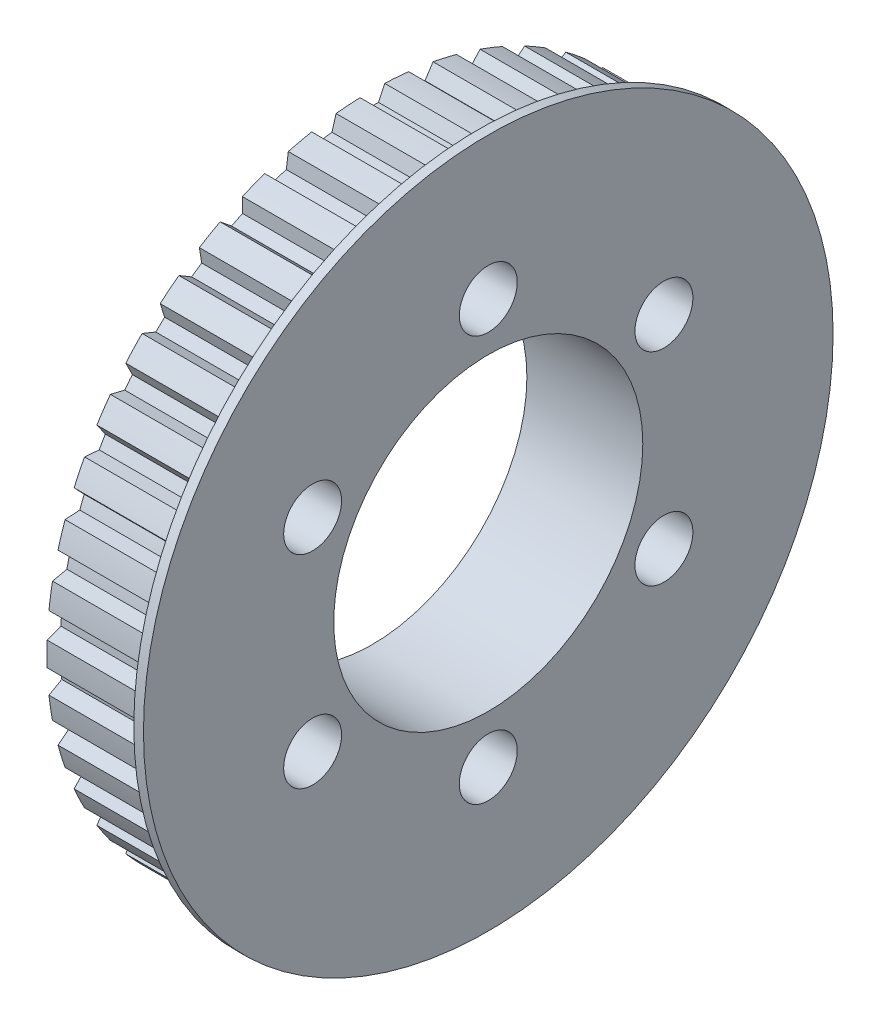
SolidWorks part; units mm, degrees
ref_plane "Front Plane" through (0, 0, 0) normal (0, 0, 1) x (1, 0, 0)
ref_plane "Top Plane" through (0, 0, 0) normal (0, 1, 0) x (1, 0, 0)
ref_plane "Right Plane" through (0, 0, 0) normal (1, 0, 0) x (0, 0, -1)
sketch "Sketch1" plane through (0, 0, 0) normal (1, 0, 0) x (0, 0, -1)
  line L0 (0, 33.705) -> (0, 0) construction
  circle A0 centre (0, 0) radius 33.705
  circle A1 centre (0, 0) radius 16
  point P19 (0, 0)
  dimension "D1" = 67.41
  dimension "D2" = 32
extrude "Boss-Extrude1" add sketch "Sketch1" along normal blind 11
sketch "Sketch2" plane through (0, 0, 0) normal (-1, 0, 0) x (0, 0, 1)
  line L0 (0, 0) -> (0, 33.705) construction
  line L1 (1.2794, 33.6807) -> (0.635, 32.2988)
  line L2 (-1.2794, 33.6807) -> (-0.635, 32.2988)
  line L3 (6.2849, 33.1138) -> (5.4417, 31.8434)
  line L4 (3.7548, 33.4952) -> (4.186, 32.0326)
  line L5 (11.1501, 31.8073) -> (10.127, 30.6767)
  line L6 (8.705, 32.5615) -> (8.9135, 31.051)
  line L7 (15.7662, 29.7902) -> (14.586, 28.8247)
  line L8 (13.4608, 30.9004) -> (13.4418, 29.3757)
  line L9 (20.0301, 27.1076) -> (18.7192, 26.3288)
  line L10 (17.916, 28.549) -> (17.6699, 27.0442)
  line L11 (23.8465, 23.8195) -> (22.4342, 23.2448)
  line L12 (21.9709, 25.5599) -> (21.5033, 24.1085)
  line L13 (27.1303, 19.9993) -> (25.6481, 19.6415)
  line L14 (25.535, 21.9998) -> (24.8563, 20.6344)
  line L15 (29.808, 15.7324) -> (28.289, 15.5995)
  line L16 (28.5287, 17.9483) -> (27.6541, 16.6993)
  line L17 (31.8199, 11.114) -> (30.298, 11.209)
  line L18 (30.8851, 13.4959) -> (29.8341, 12.3911)
  line L19 (33.121, 6.2474) -> (31.6303, 6.5681)
  line L20 (32.5516, 8.742) -> (31.3477, 7.8062)
  line L21 (33.6821, 1.2412) -> (32.2559, 1.7805)
  line L22 (33.4909, 3.7928) -> (32.161, 3.0469)
  line L23 (33.4909, -3.7928) -> (32.161, -3.0469)
  line L24 (33.6821, -1.2412) -> (32.2559, -1.7805)
  line L25 (32.5516, -8.742) -> (31.3477, -7.8062)
  line L26 (33.121, -6.2474) -> (31.6303, -6.5681)
  line L27 (30.8851, -13.4959) -> (29.8341, -12.3911)
  line L28 (31.8199, -11.114) -> (30.298, -11.209)
  line L29 (28.5287, -17.9483) -> (27.6541, -16.6993)
  line L30 (29.808, -15.7324) -> (28.289, -15.5995)
  line L31 (25.535, -21.9998) -> (24.8563, -20.6344)
  line L32 (27.1303, -19.9993) -> (25.6481, -19.6415)
  line L33 (21.9709, -25.5599) -> (21.5033, -24.1085)
  line L34 (23.8465, -23.8195) -> (22.4342, -23.2448)
  line L35 (17.916, -28.549) -> (17.6699, -27.0442)
  line L36 (20.0301, -27.1076) -> (18.7192, -26.3288)
  line L37 (13.4608, -30.9004) -> (13.4418, -29.3757)
  line L38 (15.7662, -29.7902) -> (14.586, -28.8247)
  line L39 (8.705, -32.5615) -> (8.9135, -31.051)
  line L40 (11.1501, -31.8073) -> (10.127, -30.6767)
  line L41 (3.7548, -33.4952) -> (4.186, -32.0326)
  line L42 (6.2849, -33.1138) -> (5.4417, -31.8434)
  line L43 (-1.2794, -33.6807) -> (-0.635, -32.2988)
  line L44 (1.2794, -33.6807) -> (0.635, -32.2988)
  line L45 (-6.2849, -33.1138) -> (-5.4417, -31.8434)
  line L46 (-3.7548, -33.4952) -> (-4.186, -32.0326)
  line L47 (-11.1501, -31.8073) -> (-10.127, -30.6767)
  line L48 (-8.705, -32.5615) -> (-8.9135, -31.051)
  line L49 (-15.7662, -29.7902) -> (-14.586, -28.8247)
  line L50 (-13.4608, -30.9004) -> (-13.4418, -29.3757)
  line L51 (-20.0301, -27.1076) -> (-18.7192, -26.3288)
  line L52 (-17.916, -28.549) -> (-17.6699, -27.0442)
  line L53 (-23.8465, -23.8195) -> (-22.4342, -23.2448)
  line L54 (-21.9709, -25.5599) -> (-21.5033, -24.1085)
  line L55 (-27.1303, -19.9993) -> (-25.6481, -19.6415)
  line L56 (-25.535, -21.9998) -> (-24.8563, -20.6344)
  line L57 (-29.808, -15.7324) -> (-28.289, -15.5995)
  line L58 (-28.5287, -17.9483) -> (-27.6541, -16.6993)
  line L59 (-31.8199, -11.114) -> (-30.298, -11.209)
  line L60 (-30.8851, -13.4959) -> (-29.8341, -12.3911)
  line L61 (-33.121, -6.2474) -> (-31.6303, -6.5681)
  line L62 (-32.5516, -8.742) -> (-31.3477, -7.8062)
  line L63 (-33.6821, -1.2412) -> (-32.2559, -1.7805)
  line L64 (-33.4909, -3.7928) -> (-32.161, -3.0469)
  line L65 (-33.4909, 3.7928) -> (-32.161, 3.0469)
  line L66 (-33.6821, 1.2412) -> (-32.2559, 1.7805)
  line L67 (-32.5516, 8.742) -> (-31.3477, 7.8062)
  line L68 (-33.121, 6.2474) -> (-31.6303, 6.5681)
  line L69 (-30.8851, 13.4959) -> (-29.8341, 12.3911)
  line L70 (-31.8199, 11.114) -> (-30.298, 11.209)
  line L71 (-28.5287, 17.9483) -> (-27.6541, 16.6993)
  line L72 (-29.808, 15.7324) -> (-28.289, 15.5995)
  line L73 (-25.535, 21.9998) -> (-24.8563, 20.6344)
  line L74 (-27.1303, 19.9993) -> (-25.6481, 19.6415)
  line L75 (-21.9709, 25.5599) -> (-21.5033, 24.1085)
  line L76 (-23.8465, 23.8195) -> (-22.4342, 23.2448)
  line L77 (-17.916, 28.549) -> (-17.6699, 27.0442)
  line L78 (-20.0301, 27.1076) -> (-18.7192, 26.3288)
  line L79 (-13.4608, 30.9004) -> (-13.4418, 29.3757)
  line L80 (-15.7662, 29.7902) -> (-14.586, 28.8247)
  line L81 (-8.705, 32.5615) -> (-8.9135, 31.051)
  line L82 (-11.1501, 31.8073) -> (-10.127, 30.6767)
  line L83 (-3.7548, 33.4952) -> (-4.186, 32.0326)
  line L84 (-6.2849, 33.1138) -> (-5.4417, 31.8434)
  circle A0 centre (0, 0) radius 33.705 construction
  arc A1 (1.2794, 33.6807) -> (-1.2794, 33.6807) centre (0, 0) ccw
  arc A2 (0.635, 32.2988) -> (-0.635, 32.2988) centre (0, 0) ccw
  arc A3 (6.2849, 33.1138) -> (3.7548, 33.4952) centre (0, 0) ccw
  arc A4 (5.4417, 31.8434) -> (4.186, 32.0326) centre (0, 0) ccw
  arc A5 (11.1501, 31.8073) -> (8.705, 32.5615) centre (0, 0) ccw
  arc A6 (10.127, 30.6767) -> (8.9135, 31.051) centre (0, 0) ccw
  arc A7 (15.7662, 29.7902) -> (13.4608, 30.9004) centre (0, 0) ccw
  arc A8 (14.586, 28.8247) -> (13.4418, 29.3757) centre (0, 0) ccw
  arc A9 (20.0301, 27.1076) -> (17.916, 28.549) centre (0, 0) ccw
  arc A10 (18.7192, 26.3288) -> (17.6699, 27.0442) centre (0, 0) ccw
  arc A11 (23.8465, 23.8195) -> (21.9709, 25.5599) centre (0, 0) ccw
  arc A12 (22.4342, 23.2448) -> (21.5033, 24.1085) centre (0, 0) ccw
  arc A13 (27.1303, 19.9993) -> (25.535, 21.9998) centre (0, 0) ccw
  arc A14 (25.6481, 19.6415) -> (24.8563, 20.6344) centre (0, 0) ccw
  arc A15 (29.808, 15.7324) -> (28.5287, 17.9483) centre (0, 0) ccw
  arc A16 (28.289, 15.5995) -> (27.6541, 16.6993) centre (0, 0) ccw
  arc A17 (31.8199, 11.114) -> (30.8851, 13.4959) centre (0, 0) ccw
  arc A18 (30.298, 11.209) -> (29.8341, 12.3911) centre (0, 0) ccw
  arc A19 (33.121, 6.2474) -> (32.5516, 8.742) centre (0, 0) ccw
  arc A20 (31.6303, 6.5681) -> (31.3477, 7.8062) centre (0, 0) ccw
  arc A21 (33.6821, 1.2412) -> (33.4909, 3.7928) centre (0, 0) ccw
  arc A22 (32.2559, 1.7805) -> (32.161, 3.0469) centre (0, 0) ccw
  arc A23 (33.4909, -3.7928) -> (33.6821, -1.2412) centre (0, 0) ccw
  arc A24 (32.161, -3.0469) -> (32.2559, -1.7805) centre (0, 0) ccw
  arc A25 (32.5516, -8.742) -> (33.121, -6.2474) centre (0, 0) ccw
  arc A26 (31.3477, -7.8062) -> (31.6303, -6.5681) centre (0, 0) ccw
  arc A27 (30.8851, -13.4959) -> (31.8199, -11.114) centre (0, 0) ccw
  arc A28 (29.8341, -12.3911) -> (30.298, -11.209) centre (0, 0) ccw
  arc A29 (28.5287, -17.9483) -> (29.808, -15.7324) centre (0, 0) ccw
  arc A30 (27.6541, -16.6993) -> (28.289, -15.5995) centre (0, 0) ccw
  arc A31 (25.535, -21.9998) -> (27.1303, -19.9993) centre (0, 0) ccw
  arc A32 (24.8563, -20.6344) -> (25.6481, -19.6415) centre (0, 0) ccw
  arc A33 (21.9709, -25.5599) -> (23.8465, -23.8195) centre (0, 0) ccw
  arc A34 (21.5033, -24.1085) -> (22.4342, -23.2448) centre (0, 0) ccw
  arc A35 (17.916, -28.549) -> (20.0301, -27.1076) centre (0, 0) ccw
  arc A36 (17.6699, -27.0442) -> (18.7192, -26.3288) centre (0, 0) ccw
  arc A37 (13.4608, -30.9004) -> (15.7662, -29.7902) centre (0, 0) ccw
  arc A38 (13.4418, -29.3757) -> (14.586, -28.8247) centre (0, 0) ccw
  arc A39 (8.705, -32.5615) -> (11.1501, -31.8073) centre (0, 0) ccw
  arc A40 (8.9135, -31.051) -> (10.127, -30.6767) centre (0, 0) ccw
  arc A41 (3.7548, -33.4952) -> (6.2849, -33.1138) centre (0, 0) ccw
  arc A42 (4.186, -32.0326) -> (5.4417, -31.8434) centre (0, 0) ccw
  arc A43 (-1.2794, -33.6807) -> (1.2794, -33.6807) centre (0, 0) ccw
  arc A44 (-0.635, -32.2988) -> (0.635, -32.2988) centre (0, 0) ccw
  arc A45 (-6.2849, -33.1138) -> (-3.7548, -33.4952) centre (0, 0) ccw
  arc A46 (-5.4417, -31.8434) -> (-4.186, -32.0326) centre (0, 0) ccw
  arc A47 (-11.1501, -31.8073) -> (-8.705, -32.5615) centre (0, 0) ccw
  arc A48 (-10.127, -30.6767) -> (-8.9135, -31.051) centre (0, 0) ccw
  arc A49 (-15.7662, -29.7902) -> (-13.4608, -30.9004) centre (0, 0) ccw
  arc A50 (-14.586, -28.8247) -> (-13.4418, -29.3757) centre (0, 0) ccw
  arc A51 (-20.0301, -27.1076) -> (-17.916, -28.549) centre (0, 0) ccw
  arc A52 (-18.7192, -26.3288) -> (-17.6699, -27.0442) centre (0, 0) ccw
  arc A53 (-23.8465, -23.8195) -> (-21.9709, -25.5599) centre (0, 0) ccw
  arc A54 (-22.4342, -23.2448) -> (-21.5033, -24.1085) centre (0, 0) ccw
  arc A55 (-27.1303, -19.9993) -> (-25.535, -21.9998) centre (0, 0) ccw
  arc A56 (-25.6481, -19.6415) -> (-24.8563, -20.6344) centre (0, 0) ccw
  arc A57 (-29.808, -15.7324) -> (-28.5287, -17.9483) centre (0, 0) ccw
  arc A58 (-28.289, -15.5995) -> (-27.6541, -16.6993) centre (0, 0) ccw
  arc A59 (-31.8199, -11.114) -> (-30.8851, -13.4959) centre (0, 0) ccw
  arc A60 (-30.298, -11.209) -> (-29.8341, -12.3911) centre (0, 0) ccw
  arc A61 (-33.121, -6.2474) -> (-32.5516, -8.742) centre (0, 0) ccw
  arc A62 (-31.6303, -6.5681) -> (-31.3477, -7.8062) centre (0, 0) ccw
  arc A63 (-33.6821, -1.2412) -> (-33.4909, -3.7928) centre (0, 0) ccw
  arc A64 (-32.2559, -1.7805) -> (-32.161, -3.0469) centre (0, 0) ccw
  arc A65 (-33.4909, 3.7928) -> (-33.6821, 1.2412) centre (0, 0) ccw
  arc A66 (-32.161, 3.0469) -> (-32.2559, 1.7805) centre (0, 0) ccw
  arc A67 (-32.5516, 8.742) -> (-33.121, 6.2474) centre (0, 0) ccw
  arc A68 (-31.3477, 7.8062) -> (-31.6303, 6.5681) centre (0, 0) ccw
  arc A69 (-30.8851, 13.4959) -> (-31.8199, 11.114) centre (0, 0) ccw
  arc A70 (-29.8341, 12.3911) -> (-30.298, 11.209) centre (0, 0) ccw
  arc A71 (-28.5287, 17.9483) -> (-29.808, 15.7324) centre (0, 0) ccw
  arc A72 (-27.6541, 16.6993) -> (-28.289, 15.5995) centre (0, 0) ccw
  arc A73 (-25.535, 21.9998) -> (-27.1303, 19.9993) centre (0, 0) ccw
  arc A74 (-24.8563, 20.6344) -> (-25.6481, 19.6415) centre (0, 0) ccw
  arc A75 (-21.9709, 25.5599) -> (-23.8465, 23.8195) centre (0, 0) ccw
  arc A76 (-21.5033, 24.1085) -> (-22.4342, 23.2448) centre (0, 0) ccw
  arc A77 (-17.916, 28.549) -> (-20.0301, 27.1076) centre (0, 0) ccw
  arc A78 (-17.6699, 27.0442) -> (-18.7192, 26.3288) centre (0, 0) ccw
  arc A79 (-13.4608, 30.9004) -> (-15.7662, 29.7902) centre (0, 0) ccw
  arc A80 (-13.4418, 29.3757) -> (-14.586, 28.8247) centre (0, 0) ccw
  arc A81 (-8.705, 32.5615) -> (-11.1501, 31.8073) centre (0, 0) ccw
  arc A82 (-8.9135, 31.051) -> (-10.127, 30.6767) centre (0, 0) ccw
  arc A83 (-3.7548, 33.4952) -> (-6.2849, 33.1138) centre (0, 0) ccw
  arc A84 (-4.186, 32.0326) -> (-5.4417, 31.8434) centre (0, 0) ccw
  point P10 (0, 32.305)
  point P18 (4.8148, 31.9442)
  point P23 (9.5221, 30.8698)
  point P28 (14.0166, 29.1058)
  point P33 (18.1981, 26.6916)
  point P38 (21.973, 23.6812)
  point P43 (25.2571, 20.1418)
  point P48 (27.977, 16.1525)
  point P53 (30.0719, 11.8023)
  point P58 (31.495, 7.1885)
  point P63 (32.2147, 2.4142)
  point P68 (32.2147, -2.4142)
  point P73 (31.495, -7.1885)
  point P78 (30.0719, -11.8023)
  point P83 (27.977, -16.1525)
  point P88 (25.2571, -20.1418)
  point P93 (21.973, -23.6812)
  point P98 (18.1981, -26.6916)
  point P103 (14.0166, -29.1058)
  point P108 (9.5221, -30.8698)
  point P113 (4.8148, -31.9442)
  point P118 (0, -32.305)
  point P123 (-4.8148, -31.9442)
  point P128 (-9.5221, -30.8698)
  point P133 (-14.0166, -29.1058)
  point P138 (-18.1981, -26.6916)
  point P143 (-21.973, -23.6812)
  point P148 (-25.2571, -20.1418)
  point P153 (-27.977, -16.1525)
  point P158 (-30.0719, -11.8023)
  point P159 (0, 0)
  point P161 (-31.495, -7.1885)
  point P166 (-32.2147, -2.4142)
  point P171 (-32.2147, 2.4142)
  point P176 (-31.495, 7.1885)
  point P181 (-30.0719, 11.8023)
  point P186 (-27.977, 16.1525)
  point P191 (-25.2571, 20.1418)
  point P196 (-21.973, 23.6812)
  point P201 (-18.1981, 26.6916)
  point P206 (-14.0166, 29.1058)
  point P211 (-9.5221, 30.8698)
  point P216 (-4.8148, 31.9442)
  dimension "D1" = 1.4
  dimension "D2" = 25
  dimension "D3" = 0.635
  dimension "D4" = 42
extrude "Cut-Extrude1" cut sketch "Sketch2" against normal through all
sketch "Sketch4" plane through (11, 0, 0) normal (1, 0, 0) x (0, 0, -1)
  circle A0 centre (0, 0) radius 35.705
  circle A1 centre (0, 0) radius 16 construction
  circle A2 centre (0, 0) radius 16
  arc A3 (3.7548, 33.4952) -> (1.2794, 33.6807) centre (0, 0) ccw construction
  dimension "D1" = 2
extrude "Boss-Extrude2" add sketch "Sketch4" along normal blind 1
sketch "Sketch5" plane through (0, 0, 0) normal (-1, 0, 0) x (0, 0, 1)
  line L0 (0, 0) -> (0, -21) construction
  circle A0 centre (0, -21) radius 3
  circle A1 centre (-18.1865, -10.5) radius 3
  circle A2 centre (-18.1865, 10.5) radius 3
  circle A3 centre (0, 21) radius 3
  circle A4 centre (18.1865, 10.5) radius 3
  circle A5 centre (18.1865, -10.5) radius 3
  point P16 (0, 0)
  dimension "D1" = 6
  dimension "D2" = 21
  dimension "D3" = 6
extrude "Cut-Extrude2" cut sketch "Sketch5" against normal through all
